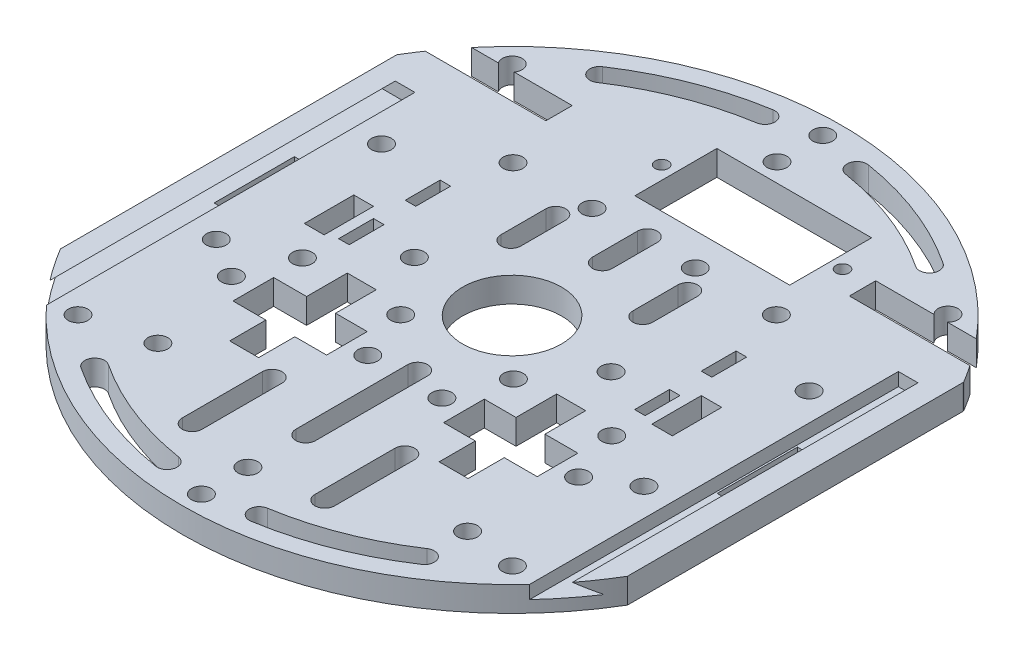
SolidWorks part; units mm, degrees
ref_plane "Plan de face" through (0, 0, 0) normal (0, 0, 1) x (1, 0, 0)
ref_plane "Plan de dessus" through (0, 0, 0) normal (0, 1, 0) x (1, 0, 0)
ref_plane "Plan de droite" through (0, 0, 0) normal (1, 0, 0) x (0, 0, -1)
sketch "Esquisse1" plane through (0, 0, 0) normal (0, 1, 0) x (1, 0, 0)
  line L0 (230, 494) -> (1150, 494) construction
  line L1 (230, 494) -> (1150, 494) construction
  line L2 (1049.7748, 1753.5) -> (2703.7748, 1753.5) construction
  line L3 (35.8344, 116.4831) -> (35.8344, 167.52)
  line L4 (121.9144, 167.4519) -> (121.9144, 116.5513)
  line L5 (88.9323, 158.6153) -> (88.9323, 151.8005) construction
  line L6 (121.9144, 116.5513) -> (121.9144, 116.4831)
  line L7 (55.7773, 128.9032) -> (60.7773, 128.9032)
  line L8 (55.7773, 128.9032) -> (55.7773, 122.7236)
  line L9 (55.7773, 122.7236) -> (60.7773, 122.7236)
  line L10 (60.7773, 122.7236) -> (60.7773, 117.2265)
  line L11 (60.7773, 117.2265) -> (65.1744, 117.2265)
  line L12 (65.1744, 117.2265) -> (65.1744, 122.7236)
  line L13 (65.1744, 122.7236) -> (69.9925, 122.7236)
  line L14 (69.9925, 122.7236) -> (69.9925, 128.9032)
  line L15 (69.9925, 128.9032) -> (65.1744, 128.9032)
  line L16 (65.1744, 128.9032) -> (65.1744, 135.081)
  line L17 (65.1744, 135.081) -> (60.7773, 135.081)
  line L18 (60.7773, 135.081) -> (60.7773, 128.9032)
  line L19 (68.9056, 158.6153) -> (68.9056, 151.8005) construction
  line L20 (70.4056, 158.6153) -> (70.4056, 151.8005)
  line L21 (67.4056, 158.6153) -> (67.4056, 151.8005)
  line L22 (78.7942, 162.6149) -> (78.7942, 155.8001) construction
  line L23 (80.2942, 162.6149) -> (80.2942, 155.8001)
  line L24 (77.2942, 162.6149) -> (77.2942, 155.8001)
  line L25 (68.7987, 115.6611) -> (68.7987, 103.5071) construction
  line L26 (70.2987, 115.6611) -> (70.2987, 103.5071)
  line L27 (67.2987, 115.6611) -> (67.2987, 103.5071)
  line L28 (39.458, 148.3706) -> (41.958, 148.3706)
  line L29 (41.958, 148.3706) -> (41.958, 136.1826)
  line L30 (41.958, 136.1826) -> (39.458, 136.1826)
  line L31 (39.458, 136.1826) -> (39.458, 148.3706)
  line L32 (55.6035, 149.0513) -> (57.2035, 149.0513)
  line L33 (54.0029, 138.3405) -> (51.0029, 138.3405)
  line L34 (54.0029, 138.3405) -> (54.0029, 145.8405)
  line L35 (54.0029, 145.8405) -> (51.0029, 145.8405)
  line L36 (51.0029, 138.3405) -> (51.0029, 145.8405)
  line L37 (55.6035, 138.9387) -> (57.2035, 138.9387)
  line L38 (55.6035, 138.9387) -> (55.6035, 144.2387)
  line L39 (55.6035, 144.2387) -> (57.2035, 144.2387)
  line L40 (57.2035, 138.9387) -> (57.2035, 144.2387)
  line L41 (55.6035, 149.0513) -> (55.6035, 154.3513)
  line L42 (55.6035, 154.3513) -> (57.2035, 154.3513)
  line L43 (57.2035, 149.0513) -> (57.2035, 154.3513)
  line L44 (35.8344, 142.0016) -> (121.9144, 142.0016) construction
  line L45 (78.8744, 142.0016) -> (78.8744, 76.4199) construction
  line L46 (78.9075, 127.6391) -> (78.9075, 110.6391) construction
  line L47 (80.4075, 127.6391) -> (80.4075, 110.6391)
  line L48 (77.4075, 127.6391) -> (77.4075, 110.6391)
  line L49 (35.8344, 162.6149) -> (121.9144, 162.6149) construction
  line L50 (87.4323, 158.6153) -> (87.4323, 151.8005)
  line L51 (90.4323, 158.6153) -> (90.4323, 151.8005)
  line L52 (88.9323, 115.6611) -> (88.9323, 103.5071) construction
  line L53 (87.4323, 115.6611) -> (87.4323, 103.5071)
  line L54 (90.4323, 115.6611) -> (90.4323, 103.5071)
  line L55 (100.5453, 149.0513) -> (100.5453, 154.3513)
  line L56 (102.1454, 154.3551) -> (100.5453, 154.3513)
  line L57 (102.1454, 149.0551) -> (102.1454, 154.3551)
  line L58 (100.5454, 138.9387) -> (100.5454, 144.2387)
  line L59 (102.1454, 144.2387) -> (100.5454, 144.2387)
  line L60 (102.1454, 138.9387) -> (102.1454, 144.2387)
  line L61 (102.1454, 138.9387) -> (100.5454, 138.9387)
  line L62 (106.8661, 138.3405) -> (106.8661, 145.8405)
  line L63 (103.7673, 145.8405) -> (106.8661, 145.8405)
  line L64 (103.7673, 138.3405) -> (103.7673, 145.8405)
  line L65 (103.7673, 138.3405) -> (106.8661, 138.3405)
  line L66 (102.1454, 149.0551) -> (100.5453, 149.0513)
  line L67 (118.245, 136.1826) -> (118.245, 148.3706)
  line L68 (115.8366, 136.1826) -> (118.245, 136.1826)
  line L69 (115.8366, 148.3706) -> (115.8366, 136.1826)
  line L70 (118.245, 148.3706) -> (115.8366, 148.3706)
  line L71 (96.9716, 135.081) -> (96.9716, 128.9032)
  line L72 (92.5745, 135.081) -> (96.9716, 135.081)
  line L73 (92.5745, 128.9032) -> (92.5745, 135.081)
  line L74 (87.7564, 128.9032) -> (92.5745, 128.9032)
  line L75 (87.7564, 122.7236) -> (87.7564, 128.9032)
  line L76 (92.5745, 122.7236) -> (87.7564, 122.7236)
  line L77 (92.5745, 117.2265) -> (92.5745, 122.7236)
  line L78 (96.9716, 117.2265) -> (92.5745, 117.2265)
  line L79 (96.9716, 122.7236) -> (96.9716, 117.2265)
  line L80 (101.9716, 122.7236) -> (96.9716, 122.7236)
  line L81 (101.9716, 128.9032) -> (101.9716, 122.7236)
  line L82 (101.9716, 128.9032) -> (96.9716, 128.9032)
  line L84 (72.4514, 167.0754) -> (95.9525, 167.0754)
  line L85 (72.4514, 167.0754) -> (72.4514, 179.5181)
  line L86 (72.4514, 179.5181) -> (95.9525, 179.5181)
  line L87 (95.9525, 167.0754) -> (95.9525, 179.5181)
  arc A1 (35.8344, 116.4831) -> (121.9144, 116.4831) centre (78.8744, 142.0016) ccw
  circle A2 centre (78.8744, 142.0016) radius 7.5
  arc A3 (121.8796, 167.5788) -> (35.8344, 167.52) centre (78.8744, 142.0016) ccw
  circle A4 centre (55.6386, 111.4684) radius 1.5
  circle A5 centre (52.4216, 125.8435) radius 1.5
  circle A6 centre (46.4093, 129.5605) radius 1.5
  circle A7 centre (45.8266, 109.1504) radius 1.5
  circle A9 centre (55.394, 133.6521) radius 1.5
  circle A10 centre (63.822, 142.2216) radius 1.5
  circle A11 centre (70.318, 133.6521) radius 1.5
  circle A12 centre (73.1582, 125.8134) radius 1.5
  circle A14 centre (78.7794, 94.9342) radius 1.5
  circle A15 centre (58.8593, 162.1633) radius 1.5
  circle A16 centre (78.7794, 101.9917) radius 1.5
  circle A17 centre (45.8266, 175.0806) radius 1.5
  circle A18 centre (78.7794, 182.3243) radius 1.5
  circle A19 centre (46.4093, 154.6416) radius 1.5
  circle A20 centre (78.7794, 189.2658) radius 1.5
  circle A21 centre (70.8644, 162.1633) radius 1.5
  arc A24 (70.4056, 158.6153) -> (67.4056, 158.6153) centre (68.9056, 158.6153) ccw
  arc A25 (67.4056, 151.8005) -> (70.4056, 151.8005) centre (68.9056, 151.8005) ccw
  arc A26 (80.2942, 162.6149) -> (77.2942, 162.6149) centre (78.7942, 162.6149) ccw
  arc A27 (77.2942, 155.8001) -> (80.2942, 155.8001) centre (78.7942, 155.8001) ccw
  arc A30 (70.2987, 115.6611) -> (67.2987, 115.6611) centre (68.7987, 115.6611) ccw
  arc A31 (67.2987, 103.5071) -> (70.2987, 103.5071) centre (68.7987, 103.5071) ccw
  arc A35 (53.8408, 103.6654) -> (71.8854, 96.6187) centre (79.1758, 141.9141) ccw construction
  arc A36 (53.0125, 102.4148) -> (71.647, 95.1377) centre (79.1758, 141.9141) ccw
  arc A37 (54.6692, 104.9159) -> (72.1238, 98.0996) centre (79.1758, 141.9141) ccw
  arc A38 (54.6692, 104.9159) -> (53.0125, 102.4148) centre (53.8408, 103.6654) ccw
  arc A39 (71.647, 95.1377) -> (72.1238, 98.0996) centre (71.8854, 96.6187) ccw
  circle A40 centre (78.9075, 110.6391) radius 1.5
  circle A41 centre (78.9075, 127.6391) radius 1.5
  arc A42 (80.4075, 127.6391) -> (77.4075, 127.6391) centre (78.9075, 127.6391) ccw
  arc A43 (77.4075, 110.6391) -> (80.4075, 110.6391) centre (78.9075, 110.6391) ccw
  arc A44 (53.8408, 180.3378) -> (71.8854, 187.3845) centre (79.1758, 142.0891) cw construction
  arc A45 (53.0125, 181.5883) -> (71.647, 188.8654) centre (79.1758, 142.0891) cw
  arc A46 (54.6692, 179.0872) -> (72.1238, 185.9035) centre (79.1758, 142.0891) cw
  arc A47 (54.6692, 179.0872) -> (53.0125, 181.5883) centre (53.8408, 180.3378) cw
  arc A48 (71.647, 188.8654) -> (72.1238, 185.9035) centre (71.8854, 187.3845) cw
  circle A49 centre (70.4056, 173.1853) radius 1
  arc A50 (87.4323, 158.6153) -> (90.4323, 158.6153) centre (88.9323, 158.6153) cw
  arc A51 (90.4323, 151.8005) -> (87.4323, 151.8005) centre (88.9323, 151.8005) cw
  arc A52 (87.4323, 115.6611) -> (90.4323, 115.6611) centre (88.9323, 115.6611) cw
  arc A53 (90.4323, 103.5071) -> (87.4323, 103.5071) centre (88.9323, 103.5071) cw
  arc A54 (103.908, 103.6654) -> (85.8635, 96.6187) centre (78.573, 141.9141) cw construction
  arc A55 (104.7364, 102.4148) -> (86.1018, 95.1377) centre (78.573, 141.9141) cw
  arc A56 (103.0797, 104.9159) -> (85.6251, 98.0996) centre (78.573, 141.9141) cw
  arc A57 (103.0797, 104.9159) -> (104.7364, 102.4148) centre (103.908, 103.6654) cw
  arc A58 (86.1018, 95.1377) -> (85.6251, 98.0996) centre (85.8635, 96.6187) cw
  arc A59 (103.908, 180.3378) -> (85.8635, 187.3845) centre (78.573, 142.0891) ccw construction
  arc A60 (104.7364, 181.5883) -> (86.1018, 188.8654) centre (78.573, 142.0891) ccw
  arc A61 (103.0797, 179.0872) -> (85.6251, 185.9035) centre (78.573, 142.0891) ccw
  arc A62 (103.0797, 179.0872) -> (104.7364, 181.5883) centre (103.908, 180.3378) ccw
  arc A63 (86.1018, 188.8654) -> (85.6251, 185.9035) centre (85.8635, 187.3845) ccw
  circle A64 centre (97.8643, 173.1853) radius 1
  circle A66 centre (86.5331, 162.1633) radius 1.5
  circle A67 centre (111.3396, 154.6416) radius 1.5
  circle A68 centre (111.7891, 175.2768) radius 1.5
  circle A69 centre (98.8379, 162.1633) radius 1.5
  circle A70 centre (84.4104, 125.8134) radius 1.5
  circle A71 centre (87.3272, 133.7572) radius 1.5
  circle A72 centre (93.7831, 142.1236) radius 1.5
  circle A73 centre (102.2561, 133.7572) radius 1.5
  circle A74 centre (105.1676, 125.8134) radius 1.5
  circle A75 centre (111.8296, 109.1035) radius 1.5
  circle A76 centre (111.3396, 129.5605) radius 1.5
  circle A78 centre (103.8661, 110.2588) radius 1.5
  arc A79 (121.8796, 167.5788) -> (121.9144, 167.4519) centre (121.6662, 167.4519) cw
  point P32 (68.9056, 155.2079)
  point P38 (55.6386, 111.4684)
  point P42 (78.7942, 159.2075)
  point P63 (68.7987, 109.5841)
  point P106 (78.9075, 119.1391)
  point P110 (62.487, 99.1788)
  point P129 (62.487, 184.8244)
  point P138 (35.8344, 167.52)
  point P139 (88.9323, 155.2079)
  point P146 (88.9323, 109.5841)
  point P154 (95.2619, 99.1788)
  point P162 (95.2619, 184.8244)
  point P225 (121.9144, 167.52)
  point P226 (102.1103, 111.4684)
  dimension "D3" = 15
  dimension "D5" = 3
  dimension "D6" = 1.5
  dimension "D7" = 1.5
  dimension "D14" = 3
  dimension "D17" = 2
  dimension "D18" = 3
  dimension "D19" = 3
  dimension "D20" = 3
  dimension "D21" = 3
  dimension "D22" = 3
  dimension "D23" = 3
  dimension "D24" = 3
  dimension "D25" = 3
  dimension "D26" = 3
  dimension "D27" = 3
  dimension "D29" = 3
  dimension "D33" = 1.5
  dimension "D35" = 3
  dimension "D2" = 51.0369
  dimension "D4" = 5
  dimension "D8" = 2.5
  dimension "D9" = 12.1879
  dimension "D10" = 3
  dimension "D11" = 7.5
  dimension "D12" = 1.6
  dimension "D13" = 5.3
  dimension "D15" = 3
  dimension "D16" = 17
  dimension "D28" = 12.1541
  dimension "D30" = 6.8148
  dimension "D31" = 43.04
  dimension "D32" = 43.04
  dimension "D34" = 6.8148
  dimension "D36" = 12.1541
  dimension "D37" = 1.6
  dimension "D38" = 5.3
extrude "Boss.-Extru.1" add sketch "Esquisse1" along normal blind 3.8 contours A79 A3 L3 A1 L6 L4 A76 A74 A72 A70 A68 A66 A55 A58 A56 A57 L54 A53 L53 A52 L51 A51 L50 A50 A45 A48 A46 A47 L57 L66 L55 L56 L60 L61 L58 L59 L33 L36
sketch "Esquisse2" plane through (0, 0, 0) normal (0, -1, 0) x (-1, 0, 0)
  line L0 (-121.9144, 167.4519) -> (-121.9144, 116.4831) construction
  line L1 (-101.9144, 174.1788) -> (-120.2144, 174.1788)
  line L2 (-101.9144, 174.1788) -> (-101.9144, 170.1788)
  line L3 (-101.9144, 170.1788) -> (-120.2144, 170.1788)
  line L4 (-120.2144, 174.1788) -> (-120.2144, 170.1788)
  line L5 (-35.8344, 116.4831) -> (-35.8344, 167.52) construction
  line L6 (-37.5344, 174.1788) -> (-55.8344, 174.1788)
  line L7 (-37.5344, 174.1788) -> (-37.5344, 170.1788)
  line L8 (-37.5344, 170.1788) -> (-55.8344, 170.1788)
  line L9 (-55.8344, 174.1788) -> (-55.8344, 170.1788)
  dimension "D1" = 1.7
  dimension "D2" = 4
  dimension "D3" = 18.3
  dimension "D5" = 1.7
  dimension "D6" = 6.6
  dimension "D8" = 18.3
extrude "Enlèv. mat.-Extru.1" cut sketch "Esquisse2" against normal blind 10
sketch "Esquisse3" plane through (0, 0, -170.1788) normal (0, 0, -1) x (-1, 0, 0)
  line L7 (-39.458, 3.8) -> (-41.7663, 3.8) construction
  line L8 (-41.7663, 3.8) -> (-41.958, 2) construction
  line L18 (-41.958, 2) -> (-37.658, 2) construction
  line L19 (-37.658, 2) -> (-39.458, 3.8) construction
  line L20 (-120.056, 2) -> (-118.256, 3.8) construction
  line L21 (-115.756, 2) -> (-120.056, 2) construction
  line L22 (-39.3751, 4) -> (-42.158, 4)
  line L23 (-78.857, 0) -> (-78.857, -13.1926) construction
  line L24 (-115.9477, 3.8) -> (-115.756, 2) construction
  line L25 (-118.256, 3.8) -> (-115.9477, 3.8) construction
  line L26 (-120.5388, 1.8) -> (-118.3388, 4)
  line L27 (-115.556, 1.8) -> (-120.5388, 1.8)
  line L28 (-115.556, 4) -> (-115.556, 1.8)
  line L29 (-118.3388, 4) -> (-115.556, 4)
  line L30 (-42.158, 4) -> (-42.158, 1.8)
  line L31 (-42.158, 1.8) -> (-37.1751, 1.8)
  line L32 (-37.1751, 1.8) -> (-39.3751, 4)
  point P13 (-41.7663, 3.8)
  point P15 (0, 0)
  dimension "D2" = 0.2
  dimension "D3" = 0.2
  dimension "D5" = 135
  dimension "D6" = 4.9828
  dimension "D7" = 2.2
extrude "Enlèv. mat.-Extru.3" cut sketch "Esquisse3" against normal blind 65.74 from offset 6.21
